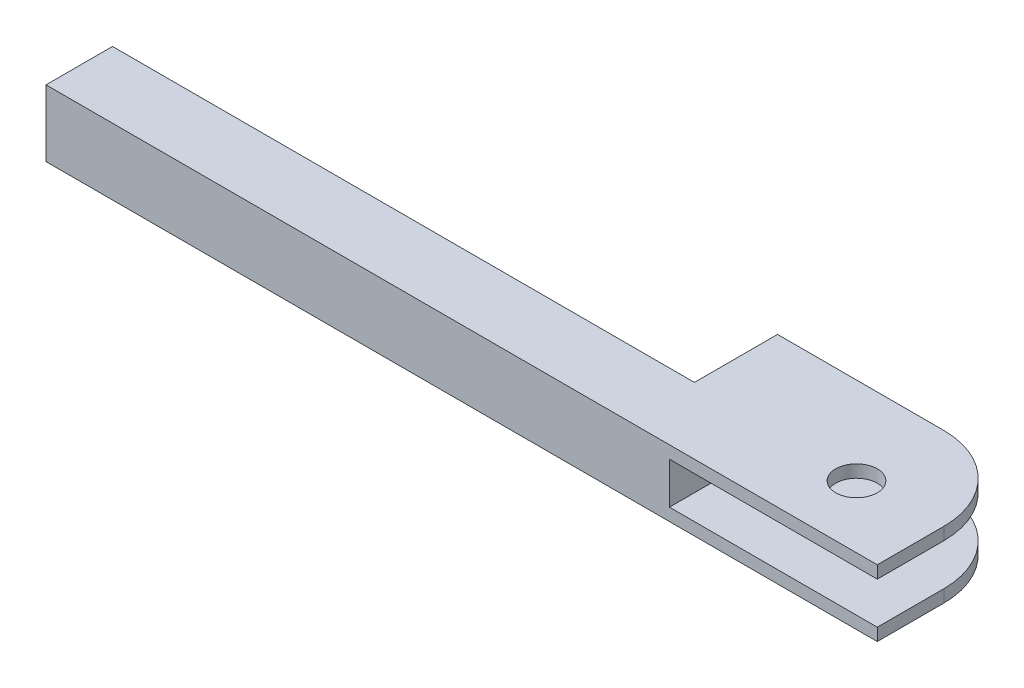
SolidWorks part; units mm, degrees
material "Copper"
ref_plane "Front Plane" through (0, 0, 0) normal (0, 0, 1) x (1, 0, 0)
ref_plane "Top Plane" through (0, 0, 0) normal (0, 1, 0) x (1, 0, 0)
ref_plane "Right Plane" through (0, 0, 0) normal (1, 0, 0) x (0, 0, -1)
sketch "Sketch1" plane through (0, 0, 0) normal (0, 1, 0) x (1, 0, 0)
  line L0 (0, 0) -> (0, 8)
  line L2 (0, -55) -> (0, 55) construction
  line L4 (0, 8) -> (70, 8)
  line L5 (70, 8) -> (70, 18)
  line L6 (70, 18) -> (100, 18)
  line L7 (100, 18) -> (100, 0)
  line L8 (-55, 0) -> (55, 0) construction
  line L9 (100, 0) -> (0, 0)
  dimension "D1" = 8
  dimension "D2" = 10
  dimension "D3" = 70
  dimension "D4" = 30
extrude "Boss-Extrude1" add sketch "Sketch1" along normal blind 8 contours L4 L5 L6 L7 L9 L0
sketch "Sketch2" plane through (0, 0, 0) normal (0, 0, 1) x (1, 0, 0)
  line L0 (100, 8) -> (100, 0) construction
  line L1 (100, 6.5) -> (75, 6.5)
  line L2 (100, 6.5) -> (100, 1.5)
  line L3 (100, 1.5) -> (75, 1.5)
  line L4 (75, 6.5) -> (75, 1.5)
  line L5 (100, 8) -> (0, 8) construction
  dimension "D1" = 5
  dimension "D2" = 1.5
  dimension "D3" = 25
extrude "Cut-Extrude1" cut sketch "Sketch2" against normal blind 35
sketch "Sketch3" plane through (0, 8, 0) normal (0, 1, 0) x (1, 0, 0)
  line L0 (100, 18) -> (100, 0) construction
  line L1 (-4.4, 0) -> (4.4, 0) construction
  circle A0 centre (90, 7.5) radius 2.5
  dimension "D1" = 10
  dimension "D2" = 7.5
  dimension "D3" = 5
extrude "Cut-Extrude2" cut sketch "Sketch3" against normal blind 35
fillet "Fillet1" radius 10 2 edges at (100, 0.75, -18) (100, 7.25, -18)
